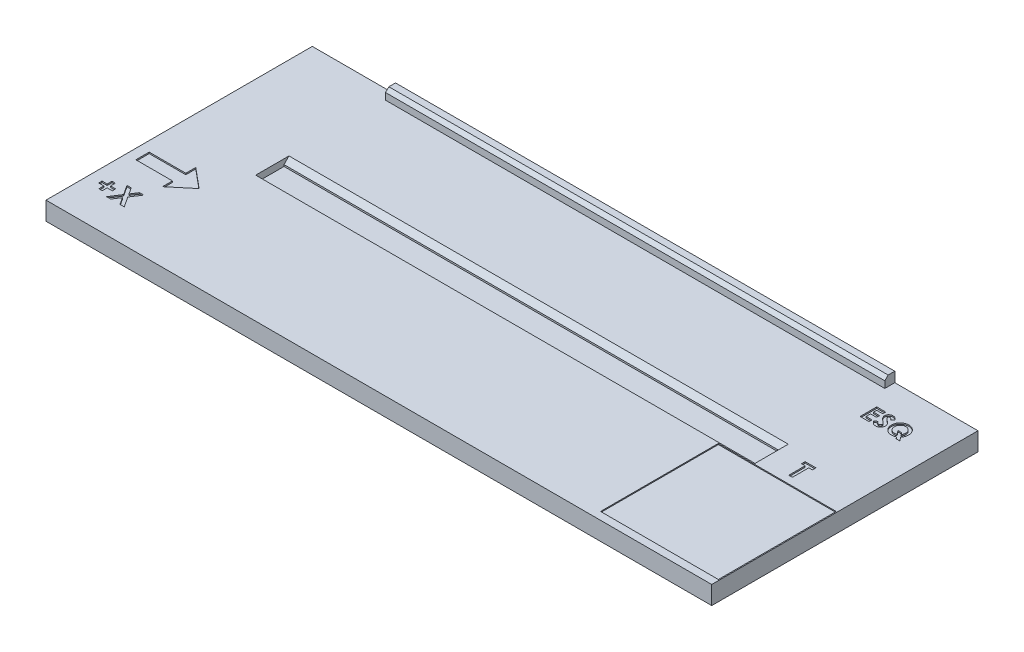
SolidWorks part; units mm, degrees
material "ABS"
ref_plane "Alzado" through (0, 0, 0) normal (0, 0, 1) x (1, 0, 0)
ref_plane "Planta" through (0, 0, 0) normal (0, 1, 0) x (1, 0, 0)
ref_plane "Vista lateral" through (0, 0, 0) normal (1, 0, 0) x (0, 0, -1)
sketch "Croquis1" plane through (0, 0, 0) normal (0, 1, 0) x (1, 0, 0)
  line L1 (-100, -40) -> (100, -40)
  line L2 (-100, -40) -> (-100, 40)
  line L3 (-100, 40) -> (100, 40)
  line L4 (100, -40) -> (100, 40)
  line L5 (-100, -40) -> (100, 40) construction
  line L6 (-100, 40) -> (100, -40) construction
  point P0 (0, 0)
extrude "Saliente-Extruir1" add sketch "Croquis1" against normal blind 6
sketch "Croquis4" plane through (0, 0, 0) normal (0, 1, 0) x (1, 0, 0)
  line L0 (-75, -0.5) -> (75, -0.5)
  line L1 (75, -0.5) -> (75, 6.5)
  line L2 (75, 6.5) -> (-75, 6.5)
  line L3 (-75, 6.5) -> (-75, -0.5)
extrude "Cortar-Extruir3" cut sketch "Croquis4" against normal blind 2
sketch "Croquis5" plane through (0, 0, 0) normal (0, 1, 0) x (1, 0, 0)
  line L0 (-75, 37) -> (75, 37)
  line L1 (75, 37) -> (75, 40)
  line L2 (75, 40) -> (-75, 40)
  line L3 (-75, 40) -> (-75, 37)
extrude "Saliente-Extruir2" add sketch "Croquis5" along normal blind 3
ref_plane "Plano inferior" through (0, -6, 0) normal (0, 1, 0) x (1, 0, 0)
sketch "Croquis8" plane through (0, -6, 0) normal (0, 1, 0) x (1, 0, 0)
  circle A0 centre (-50, 3) radius 5.2
  circle A1 centre (0, 3) radius 5.2
  circle A2 centre (50, 3) radius 5.2
sketch "Croquis9" plane through (0, -6, 0) normal (0, 1, 0) x (1, 0, 0)
  circle A0 centre (-50, 34) radius 5.2
  circle A1 centre (0, 34) radius 5.2
  circle A2 centre (50, 34) radius 5.2
sketch "Croquis10" plane through (0, -6, 0) normal (0, 1, 0) x (1, 0, 0)
  circle A0 centre (90, 32) radius 5
  circle A1 centre (90, -32) radius 5
  circle A2 centre (-90, 32) radius 5
  circle A3 centre (-90, -32) radius 5
extrude "Cortar-Extruir5" cut sketch "Croquis8" along normal blind 3.2
extrude "Cortar-Extruir6" cut sketch "Croquis9" along normal blind 4.5
extrude "Cortar-Extruir7" cut sketch "Croquis10" along normal blind 1
sketch "Croquis11" plane through (0, 0, 0) normal (0, 1, 0) x (1, 0, 0)
  line L0 (64.3, -37.7) -> (99.7, -37.7)
  line L1 (99.7, -37.7) -> (99.7, -2.3)
  line L2 (99.7, -2.3) -> (64.3, -2.3)
  line L3 (64.3, -2.3) -> (64.3, -37.7)
extrude "Cortar-Extruir8" cut sketch "Croquis11" against normal blind 0.3
chamfer "Chaflán1" distance 1.5 angle 45 2 edges at (0, 0, -6.5) (0, 0, 0.5)
chamfer "Chaflán2" distance 1 angle 45 1 edges at (0, 3, -37)
chamfer "Chaflán5" distance 0.5 angle 45 4 edges at (100, -6, 0) (0, -6, -40) (-100, -6, 0) (0, -6, 40)
sketch "Croquis12" plane through (0, 0, 0) normal (0, 1, 0) x (1, 0, 0)
  line L0 (-97, -16) -> (-86, -16)
  line L1 (-86, -16) -> (-86, -19)
  line L2 (-86, -19) -> (-80, -14)
  line L3 (-80, -14) -> (-86, -9)
  line L4 (-86, -9) -> (-86, -12)
  line L5 (-86, -12) -> (-97, -12)
  line L6 (-97, -12) -> (-97, -16)
sketch "Croquis14" plane through (0, 0, 0) normal (0, 1, 0) x (1, 0, 0)
  text T0 "T" font "Century Gothic" height 6
extrude "Cortar-Extruir9" cut sketch "Croquis12" against normal blind 0.4
extrude "Cortar-Extruir11" cut sketch "Croquis14" against normal blind 0.4
sketch "Croquis16" plane through (0, 0, 0) normal (0, 1, 0) x (1, 0, 0)
  text T0 "+X" font "Century Gothic" height 6
sketch "Croquis17" plane through (0, 0, 0) normal (0, 1, 0) x (1, 0, 0)
  text T0 "ESQ" font "Century Gothic" height 5
extrude "Cortar-Extruir13" cut sketch "Croquis16" against normal blind 0.4
extrude "Cortar-Extruir14" cut sketch "Croquis17" against normal blind 0.4
